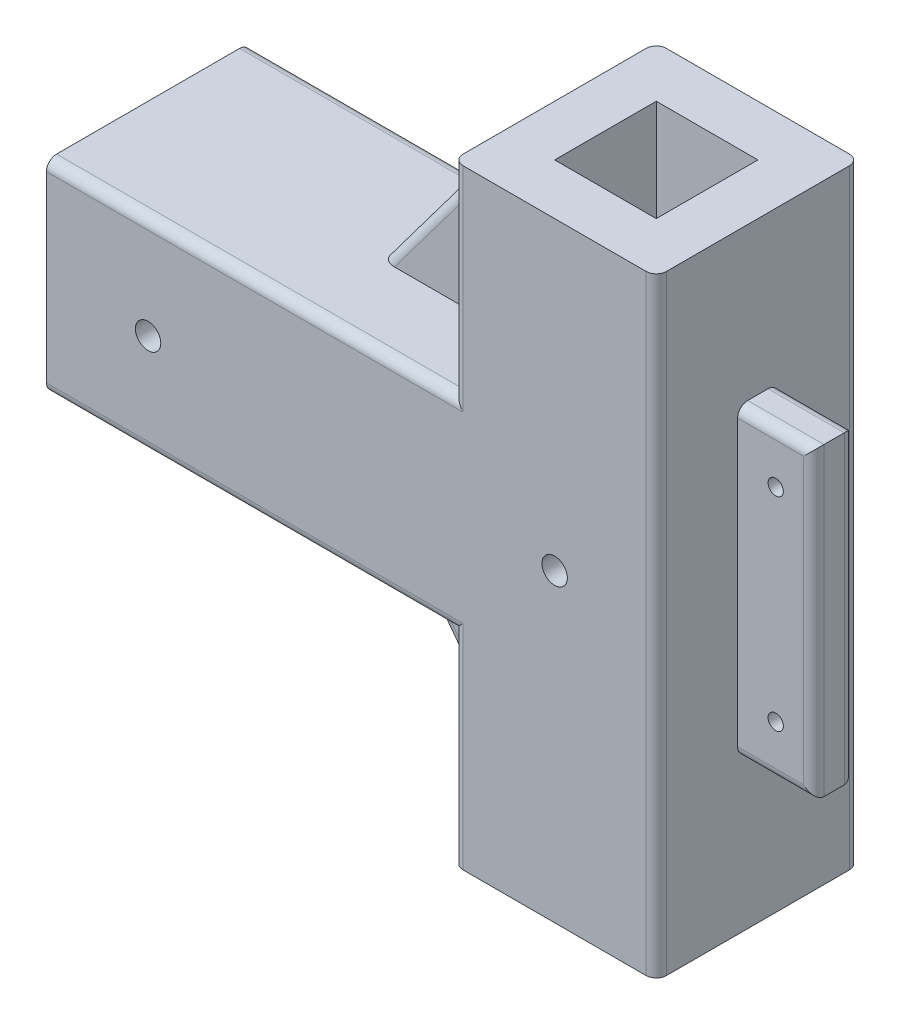
SolidWorks part; units mm, degrees
material "ABS"
ref_plane "Front Plane" through (0, 0, 0) normal (0, 0, 1) x (1, 0, 0)
ref_plane "Top Plane" through (0, 0, 0) normal (0, 1, 0) x (1, 0, 0)
ref_plane "Right Plane" through (0, 0, 0) normal (1, 0, 0) x (0, 0, -1)
sketch "Sketch1" plane through (0, 0, 0) normal (0, 1, 0) x (1, 0, 0)
  line L0 (10, 30) -> (30, 30)
  line L1 (0, 0) -> (40, 0)
  line L2 (0, 0) -> (0, 40)
  line L3 (0, 40) -> (40, 40)
  line L4 (40, 0) -> (40, 40)
  line L5 (30, 10) -> (30, 30)
  line L6 (10, 10) -> (30, 10)
  line L7 (10, 10) -> (10, 30)
  dimension "D1" = 40
  dimension "D2" = 40
  dimension "D3" = 10
extrude "Boss-Extrude1" add sketch "Sketch1" along normal blind 120
sketch "Sketch2" plane through (0, 0, 0) normal (-1, 0, 0) x (0, 0, 1)
  line L0 (-40, 120) -> (-40, 0) construction
  line L1 (-40, 80) -> (0, 80)
  line L2 (-40, 80) -> (-40, 40)
  line L3 (-40, 40) -> (0, 40)
  line L4 (0, 80) -> (0, 40)
  line L5 (0, 120) -> (0, 0) construction
  line L6 (-40, 0) -> (0, 0) construction
  line L7 (-40, 120) -> (0, 120) construction
  line L8 (-30, 70) -> (-10, 70)
  line L9 (-10, 70) -> (-10, 50)
  line L10 (-30, 50) -> (-10, 50)
  line L11 (-30, 70) -> (-30, 50)
  dimension "D1" = 40
  dimension "D2" = 40
  dimension "D3" = 10
extrude "Boss-Extrude2" add sketch "Sketch2" along normal blind 80
ref_plane "Plane4" through (0, 0, -20) normal (0, 0, 1) x (1, 0, 0)
sketch "Sketch5" plane through (0, 0, -20) normal (0, 0, 1) x (1, 0, 0)
  line L0 (0, 120) -> (0, 80)
  line L1 (0, 80) -> (-30, 80)
  line L2 (-80, 80) -> (0, 80) construction
  line L3 (-30, 80) -> (0, 120)
  line L4 (0, 0) -> (-30, 40)
  line L5 (-80, 40) -> (0, 40) construction
  line L6 (-30, 40) -> (0, 40)
  line L7 (0, 40) -> (0, 0)
  line L8 (40, 120) -> (40, 0) construction
  line L9 (40, 90) -> (55, 90)
  line L10 (40, 90) -> (40, 30)
  line L11 (40, 30) -> (55, 30)
  line L12 (55, 90) -> (55, 30)
  line L13 (0, 120) -> (40, 120) construction
  line L14 (0, 0) -> (40, 0) construction
  circle A0 centre (47.5, 80) radius 1.5
  circle A1 centre (-10, 90) radius 1.5
  circle A2 centre (-10, 30) radius 1.5
  circle A3 centre (47.5, 40) radius 1.5
  dimension "D6" = 3
  dimension "D10" = 10
  dimension "D11" = 10
  dimension "D12" = 10
  dimension "D1" = 30
  dimension "D2" = 30
  dimension "D3" = 30
  dimension "D4" = 30
  dimension "D5" = 15
  dimension "D7" = 7.5
  dimension "D8" = 10
  dimension "D9" = 10
extrude "Boss-Extrude3" add sketch "Sketch5" along normal blind 4 and the other way blind 4
sketch "Sketch7" plane through (0, 0, 0) normal (-1, 0, 0) x (0, 0, 1)
  line L1 (-30, 50) -> (-10, 50)
  line L2 (-30, 50) -> (-30, 70)
  line L3 (-30, 70) -> (-10, 70)
  line L4 (-10, 50) -> (-10, 70)
extrude "Cut-Extrude2" cut sketch "Sketch7" against normal blind 30
sketch "Sketch8" plane through (0, 0, 0) normal (0, 0, 1) x (1, 0, 0)
  line L0 (-80, 80) -> (0, 80) construction
  line L1 (-80, 40) -> (-80, 80) construction
  line L2 (40, 90) -> (40, 30) construction
  circle A0 centre (-60, 60) radius 2.5
  circle A1 centre (20, 60) radius 2.5
  dimension "D1" = 5
  dimension "D2" = 20
  dimension "D3" = 20
  dimension "D5" = 5
  dimension "D4" = 20
extrude "Cut-Extrude3" cut sketch "Sketch8" against normal through all
fillet "Fillet1" radius 2 1 edges at (-40, 80, 0)
fillet "Fillet2" radius 2 3 edges at (-40, 40, 0) (-40, 40, -40) (-40, 80, -40)
fillet "Fillet3" radius 2 6 edges at (40, 60, -40) (40, 60, 0) (0, 21, -40) (0, 21, 0) (0, 99, -40) (0, 99, 0)
fillet "Fillet4" radius 2 6 edges at (47.5, 30, -24) (47.5, 30, -16) (47.5, 90, -24) (47.5, 90, -16) (55, 60, -16) (55, 60, -24)
fillet "Fillet5" radius 2 4 edges at (-15, 20, -16) (-15, 20, -24) (-15, 100, -16) (-15, 100, -24)
